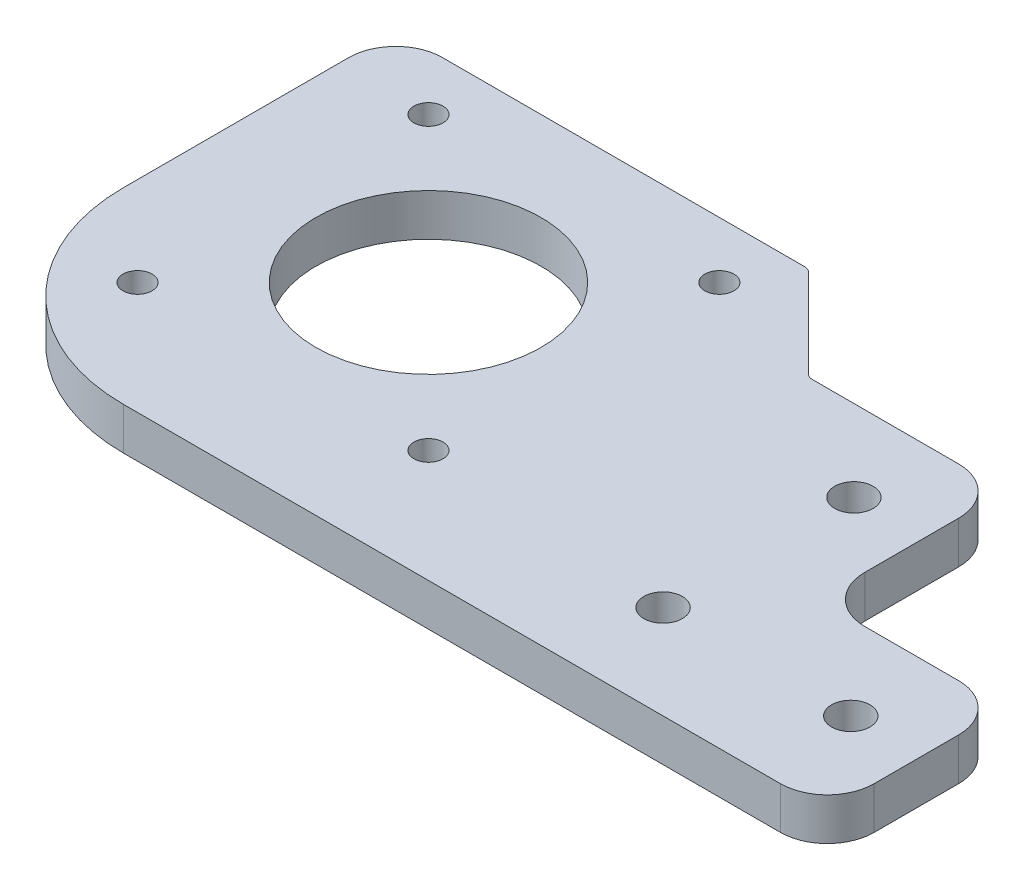
SolidWorks part; units mm, degrees
ref_plane "Front Plane" through (0, 0, 0) normal (0, 0, 1) x (1, 0, 0)
ref_plane "Top Plane" through (0, 0, 0) normal (0, 1, 0) x (1, 0, 0)
ref_plane "Right Plane" through (0, 0, 0) normal (1, 0, 0) x (0, 0, -1)
sketch "Sketch1" plane through (0, 0, 0) normal (0, 1, 0) x (1, 0, 0)
  line L0 (0, 0) -> (-95, 0)
  line L1 (-95, 0) -> (-95, 49)
  line L2 (-95, 49) -> (-51, 49)
  line L3 (-51, 49) -> (-41, 39)
  line L4 (-41, 39) -> (-20, 39)
  line L5 (-20, 39) -> (-20, 19)
  line L6 (-20, 19) -> (0, 19)
  line L7 (0, 19) -> (0, 0)
  line L8 (-7.5, 10) -> (-27.5, 10) construction
  line L9 (-27.5, 10) -> (-27.5, 30.3372) construction
  line L11 (-85.5, 12) -> (-54.5, 12) construction
  line L12 (-85.5, 12) -> (-85.5, 43) construction
  line L13 (-85.5, 43) -> (-54.5, 43) construction
  line L14 (-54.5, 12) -> (-54.5, 43) construction
  line L15 (-85.5, 12) -> (-54.5, 43) construction
  line L16 (-85.5, 43) -> (-54.5, 12) construction
  circle A0 centre (-7.5, 10) radius 2.05
  circle A1 centre (-27.5, 10) radius 2.05
  circle A2 centre (-27.5, 30.3372) radius 2.05
  circle A3 centre (-70, 27.5) radius 12
  circle A5 centre (-85.5, 43) radius 1.55
  circle A6 centre (-54.5, 43) radius 1.55
  circle A7 centre (-85.5, 12) radius 1.55
  circle A8 centre (-54.5, 12) radius 1.55
  dimension "D7" = 7.5
  dimension "D10" = 4.1
  dimension "D11" = 4.1
  dimension "D12" = 4.1
  dimension "D13" = 25
  dimension "D18" = 3.1
  dimension "D19" = 3.1
  dimension "D20" = 3.1
  dimension "D21" = 3.1
  dimension "D22" = 24
  dimension "D1" = 95
  dimension "D2" = 49
  dimension "D3" = 19
  dimension "D4" = 39
  dimension "D5" = 10
  dimension "D6" = 10
  dimension "D8" = 20
  dimension "D9" = 20
  dimension "D14" = 27.5
  dimension "D15" = 31
  dimension "D16" = 31
  dimension "D17" = 44
extrude "Boss-Extrude1" add sketch "Sketch1" along normal blind 4.5
fillet "Fillet1" radius 20 1 edges at (-95, 2.25, 0)
fillet "Fillet2" radius 5 5 edges at (-20, 2.25, -19) (0, 2.25, 0) (0, 2.25, -19) (-20, 2.25, -39) (-95, 2.25, -49)
fillet "Fillet3" radius 1 2 edges at (-41, 2.25, -39) (-51, 2.25, -49)
